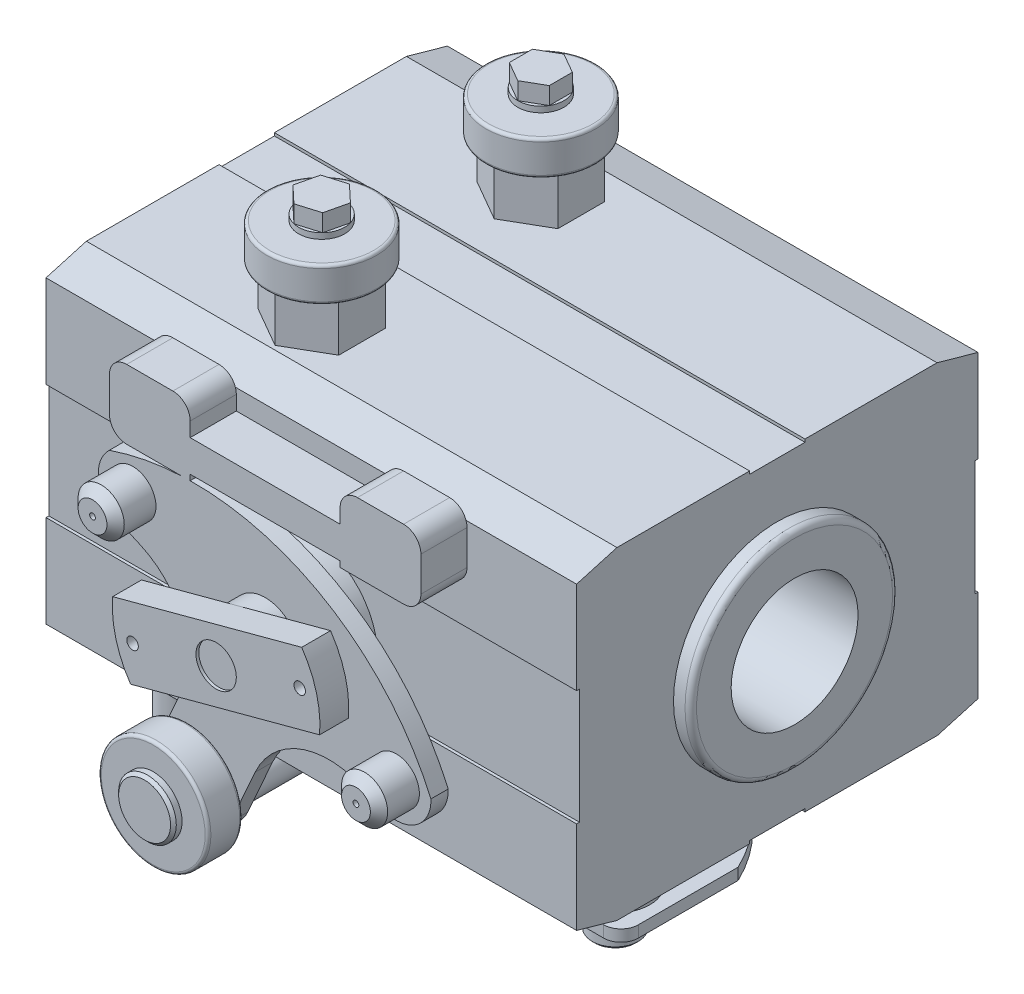
SolidWorks part; units mm, degrees
ref_plane "前视基准面" through (0, 0, 0) normal (0, 0, 1) x (1, 0, 0)
ref_plane "上视基准面" through (0, 0, 0) normal (0, 1, 0) x (1, 0, 0)
ref_plane "右视基准面" through (0, 0, 0) normal (1, 0, 0) x (0, 0, -1)
sketch "草图1" plane through (0, 0, 0) normal (0, 0, 1) x (1, 0, 0)
  line L1 (-73.0162, 7.4225) -> (18.9838, 7.4225)
  line L2 (-73.0162, 7.4225) -> (-73.0162, -48.5775)
  line L3 (-73.0162, -48.5775) -> (18.9838, -48.5775)
  line L4 (18.9838, 7.4225) -> (18.9838, -48.5775)
  dimension "D1" = 56
  dimension "D2" = 92
extrude "拉伸1" add sketch "草图1" along normal blind 69.6
sketch "草图2" plane through (18.9838, 0, 0) normal (1, 0, 0) x (0, 0, -1)
  line L0 (0, -48.5775) -> (0, 7.4225) construction
  line L1 (0, -48.5775) -> (0, -46.5775)
  line L2 (-69.6, 7.4225) -> (0, 7.4225) construction
  line L3 (-69.6, 7.4225) -> (-62.6, 7.4225)
  line L4 (-69.6, -48.5775) -> (-69.6, 7.4225) construction
  line L5 (-69.6, -48.5775) -> (-69.6, -46.5775)
  line L6 (-69.6, -48.5775) -> (0, -48.5775) construction
  line L7 (-69.6, -48.5775) -> (-62.6, -48.5775)
  line L8 (0, 5.4225) -> (-7.1025, 7.4225)
  line L9 (0, -46.5775) -> (-7, -48.5775)
  line L10 (-69.6, 5.4225) -> (-62.6, 7.4225)
  line L11 (-69.6, -46.5775) -> (-62.6, -48.5775)
  line L12 (0, 5.4225) -> (0, 7.4225)
  line L13 (-7.1025, 7.4225) -> (0, 7.4225)
  line L14 (-69.6, 5.4225) -> (-69.6, 7.4225)
  line L15 (-7, -48.5775) -> (0, -48.5775)
  dimension "D1" = 2
  dimension "D2" = 2
  dimension "D3" = 2
  dimension "D4" = 2
  dimension "D5" = 7
  dimension "D6" = 7
  dimension "D7" = 7
extrude "切除-拉伸1" cut sketch "草图2" against normal blind 100
sketch "草图3" plane through (0, -48.5775, 0) normal (0, -1, 0) x (1, 0, 0)
  line L0 (18.9838, 62.6) -> (18.9838, 7) construction
  line L1 (18.9838, 39.6) -> (18.9838, 30)
  line L2 (-73.0162, 62.6) -> (-73.0162, 7) construction
  line L3 (-73.0162, 39.6) -> (-73.0162, 30)
  line L4 (18.9838, 39.6) -> (-73.0162, 39.6)
  line L5 (18.9838, 30) -> (-73.0162, 30)
  line L6 (18.9838, 0) -> (-73.0162, 0) construction
  dimension "D1" = 9.6
  dimension "D2" = 30
extrude "切除-拉伸2" cut sketch "草图3" against normal blind 0.5
sketch "草图4" plane through (0, 7.4225, 0) normal (0, 1, 0) x (-1, 0, 0)
  line L0 (73.0162, 30) -> (-18.9838, 30) construction
  line L1 (73.0162, 30) -> (-18.9838, 30)
  line L2 (-18.9838, 39.6) -> (73.0162, 39.6) construction
  line L3 (-18.9838, 39.6) -> (73.0162, 39.6)
  line L4 (73.0162, 62.6) -> (73.0162, 7.1025) construction
  line L5 (73.0162, 39.6) -> (73.0162, 30)
  line L6 (-18.9838, 62.6) -> (-18.9838, 7.1025) construction
  line L7 (-18.9838, 39.6) -> (-18.9838, 30)
extrude "切除-拉伸3" cut sketch "草图4" against normal blind 0.5
sketch "草图5" plane through (18.9838, 0, 0) normal (1, 0, 0) x (0, 0, -1)
  line L0 (-49.8, 7.4225) -> (-49.8, 2.4225)
  line L1 (-49.8, 2.4225) -> (-19.8, 2.4225)
  line L2 (-19.8, 2.4225) -> (-19.8, 7.4225)
  line L3 (-49.8, -48.5775) -> (-49.8, -43.5775)
  line L4 (-49.8, -43.5775) -> (-19.8, -43.5775)
  line L5 (-19.8, -43.5775) -> (-19.8, -48.5775)
  line L16 (-7.1025, 7.4225) -> (-30, 7.4225)
  line L17 (-30, 7.4225) -> (-30, 6.9225)
  line L18 (-30, 6.9225) -> (-39.6, 6.9225)
  line L19 (-39.6, 6.9225) -> (-39.6, 7.4225)
  line L20 (-39.6, 7.4225) -> (-62.6, 7.4225)
  line L21 (-62.6, 7.4225) -> (-69.6, 5.4225)
  line L22 (-69.6, 5.4225) -> (-69.6, -46.5775)
  line L23 (-69.6, -46.5775) -> (-62.6, -48.5775)
  line L24 (-62.6, -48.5775) -> (-39.6, -48.5775)
  line L25 (-39.6, -48.5775) -> (-39.6, -48.0775)
  line L26 (-39.6, -48.0775) -> (-30, -48.0775)
  line L27 (-30, -48.0775) -> (-30, -48.5775)
  line L28 (-30, -48.5775) -> (-7, -48.5775)
  line L29 (-7, -48.5775) -> (0, -46.5775)
  line L30 (0, -46.5775) -> (0, 5.4225)
  line L31 (0, 5.4225) -> (-7.1025, 7.4225)
  line L32 (-7.1025, 7.4225) -> (-19.8, 7.4225)
  line L36 (-49.8, 7.4225) -> (-62.6, 7.4225)
  line L37 (-62.6, 7.4225) -> (-69.6, 5.4225)
  line L38 (-69.6, 5.4225) -> (-69.6, -46.5775)
  line L39 (-69.6, -46.5775) -> (-62.6, -48.5775)
  line L40 (-62.6, -48.5775) -> (-49.8, -48.5775)
  line L44 (-19.8, -48.5775) -> (-7, -48.5775)
  line L45 (-7, -48.5775) -> (0, -46.5775)
  line L46 (0, -46.5775) -> (0, 5.4225)
  line L47 (0, 5.4225) -> (-7.1025, 7.4225)
  dimension "D2" = 5
  dimension "D3" = 5
  dimension "D4" = 19.8
  dimension "D5" = 30
  dimension "D6" = 30
  dimension "D7" = 19.8
  dimension "D1" = 0
extrude "切除-拉伸4" cut sketch "草图5" against normal blind 3
sketch "草图6" plane through (-73.0162, 0, 0) normal (-1, 0, 0) x (0, 0, 1)
  line L0 (19.8, 2.4225) -> (49.8, 2.4225) construction
  line L1 (19.8, 2.4225) -> (49.8, 2.4225)
  line L2 (49.8, 2.4225) -> (49.8, 7.4225) construction
  line L3 (49.8, 2.4225) -> (49.8, 7.4225)
  line L4 (19.8, 7.4225) -> (19.8, 2.4225) construction
  line L5 (19.8, 7.4225) -> (19.8, 2.4225)
  line L6 (49.8, -43.5775) -> (19.8, -43.5775) construction
  line L7 (49.8, -43.5775) -> (19.8, -43.5775)
  line L8 (49.8, -48.5775) -> (49.8, -43.5775) construction
  line L9 (49.8, -48.5775) -> (49.8, -43.5775)
  line L10 (19.8, -43.5775) -> (19.8, -48.5775) construction
  line L11 (19.8, -43.5775) -> (19.8, -48.5775)
  line L16 (39.6, 6.9225) -> (30, 6.9225)
  line L17 (30, 6.9225) -> (30, 7.4225)
  line L18 (30, 7.4225) -> (7.1025, 7.4225)
  line L19 (7.1025, 7.4225) -> (0, 5.4225)
  line L20 (0, 5.4225) -> (0, -46.5775)
  line L21 (0, -46.5775) -> (7, -48.5775)
  line L22 (7, -48.5775) -> (30, -48.5775)
  line L23 (30, -48.5775) -> (30, -48.0775)
  line L24 (30, -48.0775) -> (39.6, -48.0775)
  line L25 (39.6, -48.0775) -> (39.6, -48.5775)
  line L26 (39.6, -48.5775) -> (62.6, -48.5775)
  line L27 (62.6, -48.5775) -> (69.6, -46.5775)
  line L28 (69.6, -46.5775) -> (69.6, 5.4225)
  line L29 (69.6, 5.4225) -> (62.6, 7.4225)
  line L30 (62.6, 7.4225) -> (39.6, 7.4225)
  line L31 (39.6, 7.4225) -> (39.6, 6.9225)
  line L34 (19.8, 7.4225) -> (7.1025, 7.4225)
  line L35 (7.1025, 7.4225) -> (0, 5.4225)
  line L36 (0, 5.4225) -> (0, -46.5775)
  line L37 (0, -46.5775) -> (7, -48.5775)
  line L38 (7, -48.5775) -> (19.8, -48.5775)
  line L42 (49.8, -48.5775) -> (62.6, -48.5775)
  line L43 (62.6, -48.5775) -> (69.6, -46.5775)
  line L44 (69.6, -46.5775) -> (69.6, 5.4225)
  line L45 (69.6, 5.4225) -> (62.6, 7.4225)
  line L46 (62.6, 7.4225) -> (49.8, 7.4225)
  dimension "D1" = 0
extrude "切除-拉伸5" cut sketch "草图6" against normal blind 3
sketch "草图7" plane through (-70.0162, 0, 0) normal (-1, 0, 0) x (0, 0, 1)
  line L1 (69.6, -46.5775) -> (69.6, 5.4225) construction
  line L3 (62.6, 7.4225) -> (49.8, 7.4225) construction
  circle A0 centre (34.8, -20.5775) radius 11
  dimension "D1" = 22
  dimension "D3" = 28
  dimension "D2" = 34.8
extrude "切除-拉伸6" cut sketch "草图7" against normal blind 100
sketch "草图10" plane through (0, 0, 0) normal (0, 0, -1) x (-1, 0, 0)
  line L3 (70.0162, -48.5775) -> (-15.9838, -48.5775) construction
  line L4 (52.0162, -38.5775) -> (2.0162, -38.5775) construction
  line L5 (52.0162, -38.5775) -> (52.0162, -2.5775) construction
  line L6 (70.0162, 5.4225) -> (70.0162, -46.5775) construction
  circle A0 centre (52.0162, -38.5775) radius 3
  circle A1 centre (2.0162, -38.5775) radius 3
  circle A2 centre (52.0162, -2.5775) radius 3
  circle A3 centre (2.0162, -2.5775) radius 3
  dimension "D1" = 18
  dimension "D2" = 10
  dimension "D3" = 90
  dimension "D4" = 50
extrude "切除-拉伸8" cut sketch "草图10" against normal blind 15
sketch "草图11" plane through (0, 0, 0) normal (0, 0, -1) x (-1, 0, 0)
  line L0 (70.0162, 5.4225) -> (70.0162, -46.5775) construction
  line L1 (70.0162, -10.5775) -> (70.0162, -30.5775)
  line L2 (-15.9838, -46.5775) -> (-15.9838, 5.4225) construction
  line L3 (-15.9838, -30.5775) -> (-15.9838, -10.5775)
  line L4 (-15.9838, -10.5775) -> (70.0162, -10.5775)
  line L5 (-15.9838, -30.5775) -> (70.0162, -30.5775)
  line L6 (70.0162, 7.4225) -> (-15.9838, 7.4225) construction
  dimension "D1" = 18
  dimension "D2" = 20
extrude "切除-拉伸9" cut sketch "草图11" against normal blind 0.5
sketch "草图12" plane through (0, 0, 69.6) normal (0, 0, 1) x (1, 0, 0)
  line L0 (-70.0162, -10.5775) -> (15.9838, -10.5775) construction
  line L1 (-70.0162, -10.5775) -> (15.9838, -10.5775)
  line L2 (15.9838, -30.5775) -> (-70.0162, -30.5775) construction
  line L3 (15.9838, -30.5775) -> (-70.0162, -30.5775)
  line L4 (15.9838, 5.4225) -> (15.9838, -46.5775) construction
  line L5 (15.9838, -10.5775) -> (15.9838, -30.5775)
  line L6 (-70.0162, -46.5775) -> (-70.0162, 5.4225) construction
  line L7 (-70.0162, -30.5775) -> (-70.0162, -10.5775)
extrude "切除-拉伸10" cut sketch "草图12" against normal blind 0.5
sketch "草图14" plane through (0, -48.5775, 0) normal (0, -1, 0) x (1, 0, 0)
  line L1 (18.9838, 49.8) -> (18.9838, 39.6) construction
  line L2 (15.9838, 69.6) -> (-70.0162, 69.6) construction
  circle A0 centre (-15.5162, 48.4) radius 8
  dimension "D1" = 34.5
  dimension "D2" = 21.2
extrude "切除-拉伸11" cut sketch "草图14" against normal blind 20
sketch "草图15" plane through (0, -48.5775, 0) normal (0, -1, 0) x (1, 0, 0)
  line L0 (15.9838, 69.6) -> (-70.0162, 69.6) construction
  line L1 (-70.0162, 49.8) -> (-70.0162, 62.6) construction
  circle A0 centre (-54.8162, 65.1) radius 3
  dimension "D1" = 4.5
  dimension "D2" = 15.2
extrude "切除-拉伸12" cut sketch "草图15" against normal blind 100
sketch "草图17" plane through (0, -48.5775, 0) normal (0, -1, 0) x (1, 0, 0)
  circle A0 centre (-35.5162, 48.4) radius 2
  circle A1 centre (4.4838, 48.4) radius 2
  circle A2 centre (-15.5162, 48.4) radius 8 construction
  dimension "D1" = 20
  dimension "D2" = 20
extrude "切除-拉伸14" cut sketch "草图17" against normal blind 10
sketch "草图18" plane through (0, -48.5775, 0) normal (0, -1, 0) x (1, 0, 0)
  circle A0 centre (-15.5162, 48.4) radius 9
extrude "拉伸2" add sketch "草图18" along normal blind 5
sketch "草图19" plane through (0, -53.5775, 0) normal (0, -1, 0) x (1, 0, 0)
  circle A0 centre (-15.5162, 48.4) radius 1.5
extrude "切除-拉伸15" cut sketch "草图19" against normal blind 10
sketch "草图20" plane through (0, -53.5775, 0) normal (0, -1, 0) x (1, 0, 0)
  circle A1 centre (-15.5162, 48.4) radius 9
  circle A2 centre (-15.5162, 48.4) radius 9
  dimension "D1" = 0
extrude "切除-拉伸16" cut sketch "草图20" against normal blind 2
sketch "草图21" plane through (0, 7.4225, 0) normal (0, 1, 0) x (-1, 0, 0)
  line L0 (70.0162, 19.8) -> (70.0162, 7.1025) construction
  line L1 (70.0162, 0) -> (-15.9838, 0) construction
  line L4 (70.0162, 69.6) -> (-15.9838, 69.6) construction
  line L5 (70.0162, 62.6) -> (70.0162, 49.8) construction
  circle A0 centre (41.0162, 15.8) radius 4
  circle A1 centre (41.0162, 53.8) radius 4
  dimension "D1" = 29
  dimension "D3" = 15.8
  dimension "D2" = 15.8
  dimension "D4" = 29
extrude "切除-拉伸17" cut sketch "草图21" against normal blind 10
sketch "草图23" plane through (0, 0, 69.6) normal (0, 0, 1) x (1, 0, 0)
  line L6 (-53.1579, 7.4225) -> (15.9838, 7.4225) construction
  line L11 (18.9838, 2.4225) -> (18.9838, 7.4225) construction
  line L12 (-73.0162, 7.4225) -> (-73.0162, 2.4225) construction
  circle A0 centre (-8.0162, 1.4225) radius 2.5
  circle A1 centre (-46.0162, 1.4225) radius 2.5
  dimension "D1" = 6
  dimension "D2" = 6
  dimension "D3" = 27
  dimension "D4" = 27
extrude "切除-拉伸19" cut sketch "草图23" against normal blind 6
sketch "草图24" plane through (15.9838, 0, 0) normal (1, 0, 0) x (0, 0, -1)
  line L24 (-69.6, 5.4225) -> (-69.6, -10.5775)
  line L25 (-69.6, -10.5775) -> (-69.1, -10.5775)
  line L26 (-69.1, -10.5775) -> (-69.1, -30.5775)
  line L27 (-69.1, -30.5775) -> (-69.6, -30.5775)
  line L28 (-69.6, -30.5775) -> (-69.6, -46.5775)
  line L29 (-69.6, -46.5775) -> (-62.6, -48.5775)
  line L30 (-62.6, -48.5775) -> (-49.8, -48.5775)
  line L31 (-49.8, -48.5775) -> (-49.8, -43.5775)
  line L32 (-49.8, -43.5775) -> (-19.8, -43.5775)
  line L33 (-19.8, -43.5775) -> (-19.8, -48.5775)
  line L34 (-19.8, -48.5775) -> (-7, -48.5775)
  line L35 (-7, -48.5775) -> (0, -46.5775)
  line L36 (0, -46.5775) -> (0, -30.5775)
  line L37 (0, -30.5775) -> (-0.5, -30.5775)
  line L38 (-0.5, -30.5775) -> (-0.5, -10.5775)
  line L39 (-0.5, -10.5775) -> (0, -10.5775)
  line L40 (0, -10.5775) -> (0, 5.4225)
  line L41 (0, 5.4225) -> (-7.1025, 7.4225)
  line L42 (-7.1025, 7.4225) -> (-19.8, 7.4225)
  line L43 (-19.8, 7.4225) -> (-19.8, 2.4225)
  line L44 (-19.8, 2.4225) -> (-49.8, 2.4225)
  line L45 (-49.8, 2.4225) -> (-49.8, 7.4225)
  line L46 (-49.8, 7.4225) -> (-62.6, 7.4225)
  line L47 (-62.6, 7.4225) -> (-69.6, 5.4225)
  line L48 (-69.6, 5.4225) -> (-69.6, -10.5775)
  line L49 (-69.6, -10.5775) -> (-69.1, -10.5775)
  line L50 (-69.1, -10.5775) -> (-69.1, -30.5775)
  line L51 (-69.1, -30.5775) -> (-69.6, -30.5775)
  line L52 (-69.6, -30.5775) -> (-69.6, -46.5775)
  line L53 (-69.6, -46.5775) -> (-62.6, -48.5775)
  line L54 (-62.6, -48.5775) -> (-49.8, -48.5775)
  line L55 (-49.8, -48.5775) -> (-49.8, -43.5775)
  line L56 (-49.8, -43.5775) -> (-19.8, -43.5775)
  line L57 (-19.8, -43.5775) -> (-19.8, -48.5775)
  line L58 (-19.8, -48.5775) -> (-7, -48.5775)
  line L59 (-7, -48.5775) -> (0, -46.5775)
  line L60 (0, -46.5775) -> (0, -30.5775)
  line L61 (0, -30.5775) -> (-0.5, -30.5775)
  line L62 (-0.5, -30.5775) -> (-0.5, -10.5775)
  line L63 (-0.5, -10.5775) -> (0, -10.5775)
  line L64 (0, -10.5775) -> (0, 5.4225)
  line L65 (0, 5.4225) -> (-7.1025, 7.4225)
  line L66 (-7.1025, 7.4225) -> (-19.8, 7.4225)
  line L67 (-19.8, 7.4225) -> (-19.8, 2.4225)
  line L68 (-19.8, 2.4225) -> (-49.8, 2.4225)
  line L69 (-49.8, 2.4225) -> (-49.8, 7.4225)
  line L70 (-49.8, 7.4225) -> (-62.6, 7.4225)
  line L71 (-62.6, 7.4225) -> (-69.6, 5.4225)
  circle A0 centre (-34.8, -20.5775) radius 11 construction
  circle A1 centre (-34.8, -20.5775) radius 11
  dimension "D1" = 0
extrude "拉伸3" add sketch "草图24" along normal blind 3
sketch "草图25" plane through (-70.0162, 0, 0) normal (-1, 0, 0) x (0, 0, 1)
  line L24 (69.1, -10.5775) -> (69.6, -10.5775)
  line L25 (69.6, -10.5775) -> (69.6, 5.4225)
  line L26 (69.6, 5.4225) -> (62.6, 7.4225)
  line L27 (62.6, 7.4225) -> (49.8, 7.4225)
  line L28 (49.8, 7.4225) -> (49.8, 2.4225)
  line L29 (49.8, 2.4225) -> (19.8, 2.4225)
  line L30 (19.8, 2.4225) -> (19.8, 7.4225)
  line L31 (19.8, 7.4225) -> (7.1025, 7.4225)
  line L32 (7.1025, 7.4225) -> (0, 5.4225)
  line L33 (0, 5.4225) -> (0, -10.5775)
  line L34 (0, -10.5775) -> (0.5, -10.5775)
  line L35 (0.5, -10.5775) -> (0.5, -30.5775)
  line L36 (0.5, -30.5775) -> (0, -30.5775)
  line L37 (0, -30.5775) -> (0, -46.5775)
  line L38 (0, -46.5775) -> (7, -48.5775)
  line L39 (7, -48.5775) -> (19.8, -48.5775)
  line L40 (19.8, -48.5775) -> (19.8, -43.5775)
  line L41 (19.8, -43.5775) -> (49.8, -43.5775)
  line L42 (49.8, -43.5775) -> (49.8, -48.5775)
  line L43 (49.8, -48.5775) -> (62.6, -48.5775)
  line L44 (62.6, -48.5775) -> (69.6, -46.5775)
  line L45 (69.6, -46.5775) -> (69.6, -30.5775)
  line L46 (69.6, -30.5775) -> (69.1, -30.5775)
  line L47 (69.1, -30.5775) -> (69.1, -10.5775)
  line L48 (69.1, -10.5775) -> (69.6, -10.5775)
  line L49 (69.6, -10.5775) -> (69.6, 5.4225)
  line L50 (69.6, 5.4225) -> (62.6, 7.4225)
  line L51 (62.6, 7.4225) -> (49.8, 7.4225)
  line L52 (49.8, 7.4225) -> (49.8, 2.4225)
  line L53 (49.8, 2.4225) -> (19.8, 2.4225)
  line L54 (19.8, 2.4225) -> (19.8, 7.4225)
  line L55 (19.8, 7.4225) -> (7.1025, 7.4225)
  line L56 (7.1025, 7.4225) -> (0, 5.4225)
  line L57 (0, 5.4225) -> (0, -10.5775)
  line L58 (0, -10.5775) -> (0.5, -10.5775)
  line L59 (0.5, -10.5775) -> (0.5, -30.5775)
  line L60 (0.5, -30.5775) -> (0, -30.5775)
  line L61 (0, -30.5775) -> (0, -46.5775)
  line L62 (0, -46.5775) -> (7, -48.5775)
  line L63 (7, -48.5775) -> (19.8, -48.5775)
  line L64 (19.8, -48.5775) -> (19.8, -43.5775)
  line L65 (19.8, -43.5775) -> (49.8, -43.5775)
  line L66 (49.8, -43.5775) -> (49.8, -48.5775)
  line L67 (49.8, -48.5775) -> (62.6, -48.5775)
  line L68 (62.6, -48.5775) -> (69.6, -46.5775)
  line L69 (69.6, -46.5775) -> (69.6, -30.5775)
  line L70 (69.6, -30.5775) -> (69.1, -30.5775)
  line L71 (69.1, -30.5775) -> (69.1, -10.5775)
  circle A0 centre (34.8, -20.5775) radius 11 construction
  circle A1 centre (34.8, -20.5775) radius 11
  dimension "D1" = 0
extrude "拉伸4" add sketch "草图25" along normal blind 3
sketch "草图26" plane through (-73.0162, 0, 0) normal (-1, 0, 0) x (0, 0, 1)
  circle A0 centre (34.8, -20.5775) radius 18
  circle A1 centre (34.8, -20.5775) radius 11 construction
  circle A2 centre (34.8, -20.5775) radius 11
extrude "拉伸5" add sketch "草图26" along normal blind 3
sketch "草图27" plane through (18.9838, 0, 0) normal (1, 0, 0) x (0, 0, -1)
  circle A0 centre (-34.8, -20.5775) radius 18
  circle A1 centre (-34.8, -20.5775) radius 11 construction
  circle A2 centre (-34.8, -20.5775) radius 11
extrude "拉伸6" add sketch "草图27" along normal blind 3
fillet "圆角1" radius 1 2 edges at (-76.0162, -20.5775, 52.8) (21.9838, -20.5775, 16.8)
sketch "草图28" plane through (0, -48.5775, 0) normal (0, -1, 0) x (1, 0, 0)
  circle A0 centre (4.4838, 48.4) radius 6
  circle A1 centre (-35.5162, 48.4) radius 6
extrude "拉伸7" add sketch "草图28" along normal blind 9
sketch "草图29" plane through (0, -51.5775, 0) normal (0, -1, 0) x (1, 0, 0)
  circle A1 centre (-15.5162, 48.4) radius 9
  circle A2 centre (-15.5162, 48.4) radius 9
  dimension "D1" = 0
extrude "拉伸8" add sketch "草图29" along normal blind 5
sketch "草图30" plane through (0, -56.5775, 0) normal (0, -1, 0) x (1, 0, 0)
  line L0 (-15.9113, 56.7698) -> (-11.4651, 55.7348)
  line L1 (-17.6313, 56.9563) -> (-29.3268, 6.7164)
  line L2 (-9.8396, 55.1425) -> (-21.5352, 4.9025)
  line L3 (-27.7013, 6.124) -> (-23.2552, 5.089)
  arc A1 (-29.3268, 6.7164) -> (-27.7013, 6.124) centre (-19.5832, 30.9294) ccw
  arc A2 (-9.8396, 55.1425) -> (-11.4651, 55.7348) centre (-19.5832, 30.9294) ccw
  arc A3 (-23.2552, 5.089) -> (-21.5352, 4.9025) centre (-19.5832, 30.9294) ccw
  arc A4 (-15.9113, 56.7698) -> (-17.6313, 56.9563) centre (-19.5832, 30.9294) ccw
  dimension "D1" = 8
  dimension "D2" = 52
extrude "拉伸9" add sketch "草图30" along normal blind 1
sketch "草图31" plane through (0, -57.5775, 0) normal (0, -1, 0) x (1, 0, 0)
  line L0 (-3.5162, 48.4) -> (-3.5162, 50.4)
  line L1 (9.4838, 55.4) -> (1.4838, 55.4)
  line L2 (12.4838, 52.4) -> (12.4838, 35.0959)
  line L3 (-27.5162, 48.4) -> (-27.5162, 50.4)
  line L4 (-43.5162, 52.4) -> (-43.5162, 35.0959)
  line L5 (-32.5162, 55.4) -> (-40.5162, 55.4)
  arc A0 (-32.5162, 55.4) -> (-27.5162, 50.4) centre (-32.5162, 50.4) cw
  arc A1 (-13.4483, 39.6408) -> (-21.24, 41.4546) centre (-15.5162, 48.4) ccw construction
  circle A2 centre (-15.5162, 48.4) radius 8 construction
  arc A3 (-43.5162, 35.0959) -> (12.4838, 35.0959) centre (-15.5162, 48.4) ccw
  arc A4 (-27.5162, 48.4) -> (-3.5162, 48.4) centre (-15.5162, 48.4) ccw
  arc A5 (1.4838, 55.4) -> (-3.5162, 50.4) centre (1.4838, 50.4) ccw
  arc A6 (-40.5162, 55.4) -> (-43.5162, 52.4) centre (-40.5162, 52.4) ccw
  arc A7 (9.4838, 55.4) -> (12.4838, 52.4) centre (9.4838, 52.4) cw
  point P16 (-27.5162, 55.4)
  dimension "D1" = 28
  dimension "D2" = 28
  dimension "D4" = 5
  dimension "D5" = 3
  dimension "D3" = 7
extrude "拉伸10" add sketch "草图31" along normal blind 2
sketch "草图32" plane through (0, -59.5775, 0) normal (0, -1, 0) x (1, 0, 0)
  circle A0 centre (4.4838, 48.4) radius 4
  circle A1 centre (-35.5162, 48.4) radius 4
extrude "拉伸11" add sketch "草图32" along normal blind 5
sketch "草图33" plane through (0, -64.5775, 0) normal (0, -1, 0) x (1, 0, 0)
  line L1 (-33.7841, 48.4) -> (-34.6502, 49.9)
  line L2 (-34.6502, 49.9) -> (-36.3822, 49.9)
  line L3 (-36.3822, 49.9) -> (-37.2482, 48.4)
  line L4 (-37.2482, 48.4) -> (-36.3822, 46.9)
  line L5 (-36.3822, 46.9) -> (-34.6502, 46.9)
  line L6 (-34.6502, 46.9) -> (-33.7841, 48.4)
  line L7 (5.0589, 46.7662) -> (6.1863, 48.0811)
  line L8 (6.1863, 48.0811) -> (5.6112, 49.7149)
  line L9 (5.6112, 49.7149) -> (3.9087, 50.0338)
  line L10 (3.9087, 50.0338) -> (2.7814, 48.7189)
  line L11 (2.7814, 48.7189) -> (3.3564, 47.0851)
  line L12 (3.3564, 47.0851) -> (5.0589, 46.7662)
  circle A0 centre (-35.5162, 48.4) radius 1.5 construction
  circle A1 centre (4.4838, 48.4) radius 1.5 construction
  dimension "D1" = 3
  dimension "D2" = 3
extrude "切除-拉伸20" cut sketch "草图33" against normal blind 3
chamfer "倒角1" distance 0.5 angle 45 2 edges at (4.4838, -64.5775, 44.4) (-35.5162, -64.5775, 44.4)
sketch "草图34" plane through (0, -57.5775, 0) normal (0, -1, 0) x (1, 0, 0)
  line L3 (-26.3819, 19.3666) -> (-29.3268, 6.7164)
  line L4 (-27.7013, 6.124) -> (-23.2552, 5.089)
  line L5 (-21.5352, 4.9025) -> (-18.5903, 17.5528)
  line L6 (-26.3819, 19.3666) -> (-29.3268, 6.7164)
  line L7 (-27.7013, 6.124) -> (-23.2552, 5.089)
  line L8 (-21.5352, 4.9025) -> (-18.5903, 17.5528)
  arc A3 (-26.3819, 19.3666) -> (-18.5903, 17.5528) centre (-15.5162, 48.4) ccw
  arc A4 (-29.3268, 6.7164) -> (-27.7013, 6.124) centre (-19.5832, 30.9294) ccw
  arc A5 (-23.2552, 5.089) -> (-21.5352, 4.9025) centre (-19.5832, 30.9294) ccw
  arc A6 (-26.3819, 19.3666) -> (-18.5903, 17.5528) centre (-15.5162, 48.4) ccw
  arc A7 (-29.3268, 6.7164) -> (-27.7013, 6.124) centre (-19.5832, 30.9294) ccw
  arc A8 (-23.2552, 5.089) -> (-21.5352, 4.9025) centre (-19.5832, 30.9294) ccw
  dimension "D1" = 0
extrude "拉伸12" add sketch "草图34" along normal blind 2
sketch "草图35" plane through (0, -59.5775, 0) normal (0, -1, 0) x (1, 0, 0)
  line L0 (-27.7013, 6.124) -> (-23.2552, 5.089) construction
  line L1 (-27.7013, 6.124) -> (-23.2552, 5.089)
  line L2 (-21.5352, 4.9025) -> (-18.5903, 17.5528) construction
  line L3 (-21.5352, 4.9025) -> (-18.5903, 17.5528)
  line L4 (-26.3819, 19.3666) -> (-29.3268, 6.7164) construction
  line L5 (-26.3819, 19.3666) -> (-29.3268, 6.7164)
  line L6 (-21.5352, 20.4951) -> (-21.0831, 17.9039)
  line L7 (-21.5352, 20.4951) -> (-23.0563, 18.331)
  arc A0 (-29.3268, 6.7164) -> (-27.7013, 6.124) centre (-19.5832, 30.9294) ccw construction
  arc A1 (-29.3268, 6.7164) -> (-27.7013, 6.124) centre (-19.5832, 30.9294) ccw
  arc A2 (-23.2552, 5.089) -> (-21.5352, 4.9025) centre (-19.5832, 30.9294) ccw construction
  arc A3 (-23.2552, 5.089) -> (-21.5352, 4.9025) centre (-19.5832, 30.9294) ccw
  arc A4 (-18.5903, 17.5528) -> (12.4838, 35.0959) centre (-15.5162, 48.4) ccw construction
  arc A5 (-26.3819, 19.3666) -> (-23.0563, 18.331) centre (-15.5162, 48.4) ccw
  arc A6 (-21.0831, 17.9039) -> (-18.5903, 17.5528) centre (-15.5162, 48.4) ccw
extrude "拉伸13" add sketch "草图35" along normal blind 0.5
sketch "草图36" plane through (0, -48.5775, 0) normal (0, -1, 0) x (1, 0, 0)
  arc A0 (-53.1579, 62.6) -> (-56.4745, 62.6) centre (-54.8162, 65.1) ccw construction
  arc A1 (-53.1579, 62.6) -> (-56.4745, 62.6) centre (-54.8162, 65.1) ccw
  arc A2 (-56.4745, 62.6) -> (-53.1579, 62.6) centre (-54.8162, 65.1) ccw construction
  arc A3 (-56.4745, 62.6) -> (-53.1579, 62.6) centre (-54.8162, 65.1) ccw
ref_plane "基准面1" through (-54.82, 0, 0) normal (1, 0, 0) x (0, 0, -1)
sketch "草图37" plane through (-54.82, 0, 0) normal (1, 0, 0) x (0, 0, -1)
  line L0 (-65.0156, -34.5775) -> (-65.0156, -59.5775)
  line L1 (-56.0156, -68.5775) -> (-40.0156, -68.5775)
  line L2 (-62.6, -48.5775) -> (-39.6, -48.5775) construction
  arc A0 (-56.0156, -68.5775) -> (-65.0156, -59.5775) centre (-56.0156, -59.5775) cw
  point P5 (-65.0156, -68.5775)
  dimension "D3" = 9
  dimension "D1" = 25
  dimension "D2" = 25
  dimension "D4" = 20
sweep "扫描3" add profiles "草图36" path "草图37"
sketch "草图38" plane through (0, 7.4225, 0) normal (0, 1, 0) x (-1, 0, 0)
  arc A0 (56.4745, 62.6) -> (53.1579, 62.6) centre (54.8162, 65.1) ccw construction
  arc A1 (56.4745, 62.6) -> (53.1579, 62.6) centre (54.8162, 65.1) ccw
  arc A2 (53.1579, 62.6) -> (56.4745, 62.6) centre (54.8162, 65.1) ccw construction
  arc A3 (53.1579, 62.6) -> (56.4745, 62.6) centre (54.8162, 65.1) ccw
extrude "拉伸14" add sketch "草图38" against normal blind 56
sketch "草图39" plane through (-73.0162, 0, 0) normal (-1, 0, 0) x (0, 0, 1)
  line L0 (69.6, 5.4225) -> (62.6, 7.4225) construction
  line L1 (69.6, 5.4225) -> (62.6, 7.4225)
  line L2 (68.1, 7.4225) -> (62.6, 7.4225) construction
  line L3 (69.6, 7.4225) -> (62.6, 7.4225)
  line L4 (69.6, -10.5775) -> (69.6, 5.4225) construction
  line L5 (69.6, 5.4225) -> (69.6, 7.4225)
extrude "切除-拉伸21" cut sketch "草图39" against normal blind 100
chamfer "倒角2" distance 0.5 angle 45 1 edges at (-54.8162, -65.6619, 40.0156)
sketch "草图40" plane through (0, 0, 69.6) normal (0, 0, 1) x (1, 0, 0)
  line L0 (-40.0162, -3.5775) -> (-14.0162, -3.5775)
  line L1 (-51.0162, 7.4225) -> (-43.0162, 7.4225)
  line L2 (-54.0162, 4.4225) -> (-54.0162, -1.5775)
  line L3 (-14.0162, -4.5775) -> (-3.0162, -4.5775)
  line L4 (-0.0162, 4.4225) -> (-0.0162, -1.5775)
  line L6 (-14.0162, 1.9225) -> (-14.0162, 4.4225)
  line L7 (-40.0162, -3.5775) -> (-40.0162, -4.5775)
  line L8 (-40.0162, 4.4225) -> (-40.0162, 1.9225)
  line L9 (-40.0162, 1.9225) -> (-14.0162, 1.9225)
  line L10 (-14.0162, -4.5775) -> (-14.0162, -3.5775)
  line L12 (-11.0162, 7.4225) -> (-3.0162, 7.4225)
  line L14 (-51.0162, -4.5775) -> (-40.0162, -4.5775)
  circle A1 centre (-46.0162, 1.4225) radius 2.5 construction
  circle A4 centre (-8.0162, 1.4225) radius 2.5 construction
  arc A6 (-51.0162, 7.4225) -> (-54.0162, 4.4225) centre (-51.0162, 4.4225) ccw
  arc A7 (-40.0162, 4.4225) -> (-43.0162, 7.4225) centre (-43.0162, 4.4225) ccw
  arc A10 (-3.0162, 7.4225) -> (-0.0162, 4.4225) centre (-3.0162, 4.4225) cw
  arc A11 (-14.0162, 4.4225) -> (-11.0162, 7.4225) centre (-11.0162, 4.4225) cw
  arc A12 (-3.0162, -4.5775) -> (-0.0162, -1.5775) centre (-3.0162, -1.5775) ccw
  arc A13 (-51.0162, -4.5775) -> (-54.0162, -1.5775) centre (-51.0162, -1.5775) cw
  point P30 (-14.0162, 7.4225)
  dimension "D1" = 6
  dimension "D6" = 6
  dimension "D8" = 1
  dimension "D9" = 3
  dimension "D10" = 3
  dimension "D2" = 8
  dimension "D3" = 6
  dimension "D4" = 5.5
  dimension "D5" = 8
  dimension "D7" = 6
extrude "拉伸15" add sketch "草图40" along normal blind 8
sketch "草图42" plane through (0, 0, 69.1) normal (0, 0, 1) x (1, 0, 0)
  line L1 (18.9838, -10.5775) -> (18.9838, -30.5775) construction
  line L7 (-53.1579, -48.5775) -> (18.9838, -48.5775) construction
  circle A0 centre (-27.0162, -21.5775) radius 3.5
  dimension "D1" = 46
  dimension "D2" = 27
extrude "拉伸17" add sketch "草图42" along normal blind 1.5
sketch "草图43" plane through (0, 0, 70.6) normal (0, 0, 1) x (1, 0, 0)
  circle A0 centre (-27.0162, -21.5775) radius 12.5
extrude "拉伸18" add sketch "草图43" along normal blind 4
sketch "草图44" plane through (0, 0, 74.6) normal (0, 0, 1) x (1, 0, 0)
  line L1 (-48.6456, -18.5175) -> (-52.295, -16.894)
  line L5 (-6.8066, -37.1309) -> (-10.2717, -35.5893)
  line L10 (-28.752, -42.6863) -> (-33.0268, -52.2878)
  line L12 (-41.5466, -37.0032) -> (-45.8165, -46.5935)
  arc A0 (1.7221, -31.4629) -> (-54.0425, -6.9878) centre (-39.4216, -49.4406) ccw
  arc A1 (-6.8066, -37.1309) -> (1.7221, -31.4629) centre (-4.2735, -31.6918) ccw
  circle A2 centre (-27.0162, -21.5775) radius 12.5 construction
  arc A3 (-45.8165, -46.5935) -> (-33.0268, -52.2878) centre (-39.4216, -49.4406) ccw
  arc A4 (-54.0425, -6.9878) -> (-52.295, -16.894) centre (-49.9469, -11.3726) ccw
  arc A5 (-10.2717, -35.5893) -> (-28.752, -42.6863) centre (-15.9623, -48.3806) ccw
  arc A6 (-48.6456, -18.5175) -> (-41.5466, -37.0032) centre (-54.3362, -31.3088) cw
  point P23 (-35.8506, -24.2098)
  point P34 (-35.8585, -24.2276)
  dimension "D2" = 30.5
  dimension "D3" = 14
  dimension "D7" = 89.8
extrude "拉伸19" add sketch "草图44" along normal blind 3
sketch "草图45" plane through (0, 0, 77.6) normal (0, 0, 1) x (1, 0, 0)
  circle A0 centre (-39.4216, -49.4406) radius 3.5
extrude "拉伸20" add sketch "草图45" along normal blind 1
sketch "草图46" plane through (0, 0, 78.6) normal (0, 0, 1) x (1, 0, 0)
  circle A0 centre (-39.4216, -49.4406) radius 9.5
extrude "拉伸21" add sketch "草图46" along normal blind 6
fillet "圆角3" radius 0.5 2 edges at (-29.9216, -49.4406, 84.6) (-29.9216, -49.4406, 78.6)
sketch "草图48" plane through (0, 0, 84.6) normal (0, 0, 1) x (1, 0, 0)
  circle A0 centre (-39.4216, -49.4406) radius 5
extrude "拉伸22" add sketch "草图48" along normal blind 1.5
chamfer "倒角3" distance 0.5 angle 45 1 edges at (-34.4216, -49.4406, 86.1)
sketch "草图49" plane through (0, 0, 77.6) normal (0, 0, 1) x (1, 0, 0)
  circle A0 centre (-4.2735, -31.6918) radius 4
  circle A1 centre (-49.9469, -11.3726) radius 4
extrude "拉伸23" add sketch "草图49" along normal blind 7
chamfer "倒角4" distance 1.5 angle 45 2 edges at (-45.9469, -11.3726, 84.6) (-0.2735, -31.6918, 84.6)
sketch "草图50" plane through (0, 0, 84.6) normal (0, 0, 1) x (1, 0, 0)
  circle A0 centre (-4.2735, -31.6918) radius 0.5
  circle A1 centre (-49.9469, -11.3726) radius 0.5
extrude "切除-拉伸22" cut sketch "草图50" against normal blind 3
sketch "草图51" plane through (0, 0, 77.6) normal (0, 0, 1) x (1, 0, 0)
  circle A0 centre (-27.0162, -21.5775) radius 6
extrude "拉伸24" add sketch "草图51" along normal blind 3.5
sketch "草图53" plane through (0, 0, 81.1) normal (0, 0, 1) x (1, 0, 0)
  line L1 (-41.8556, -31.7654) -> (-9.071, -22.9808)
  line L2 (-44.9614, -20.1742) -> (-12.1768, -11.3896)
  arc A0 (-9.071, -22.9808) -> (-12.1768, -11.3896) centre (-27.0162, -21.5775) ccw
  arc A3 (-44.9614, -20.1742) -> (-41.8556, -31.7654) centre (-27.0162, -21.5775) ccw
  dimension "D1" = 12
extrude "拉伸27" add sketch "草图53" along normal blind 5
sketch "草图55" plane through (0, 0, 86.1) normal (0, 0, 1) x (1, 0, 0)
  circle A0 centre (-27.0162, -21.5775) radius 3.5
extrude "切除-拉伸23" cut sketch "草图55" against normal blind 0.5
sketch "草图56" plane through (0, 0, 86.1) normal (0, 0, 1) x (1, 0, 0)
  line L0 (-41.8556, -31.7654) -> (-9.071, -22.9808) construction
  circle A0 centre (-12.5273, -17.6952) radius 1
  circle A1 centre (-41.5051, -25.4598) radius 1
  circle A4 centre (-27.0162, -21.5775) radius 3.5 construction
  dimension "D1" = 6
  dimension "D3" = 15
  dimension "D4" = 15
  dimension "D2" = 6
extrude "切除-拉伸24" cut sketch "草图56" against normal blind 5
sketch "草图57" plane through (0, 7.4225, 0) normal (0, 1, 0) x (-1, 0, 0)
  line L0 (73.0162, 39.6) -> (-18.9838, 39.6) construction
  line L1 (48.0162, 57.8415) -> (41.0162, 61.8829)
  line L2 (41.0162, 61.8829) -> (34.0162, 57.8415)
  line L3 (34.0162, 57.8415) -> (34.0162, 49.7585)
  line L4 (34.0162, 49.7585) -> (41.0162, 45.7171)
  line L5 (41.0162, 45.7171) -> (48.0162, 49.7585)
  line L6 (48.0162, 49.7585) -> (48.0162, 57.8415)
  line L7 (48.0162, 19.8415) -> (41.0162, 23.8829)
  line L8 (41.0162, 23.8829) -> (34.0162, 19.8415)
  line L9 (34.0162, 19.8415) -> (34.0162, 11.7585)
  line L10 (34.0162, 11.7585) -> (41.0162, 7.7171)
  line L11 (41.0162, 7.7171) -> (48.0162, 11.7585)
  line L12 (48.0162, 11.7585) -> (48.0162, 19.8415)
  line L13 (-18.9838, 30) -> (73.0162, 30) construction
  circle A0 centre (41.0162, 53.8) radius 7 construction
  circle A1 centre (41.0162, 15.8) radius 7 construction
  dimension "D1" = 90
  dimension "D2" = 90
  dimension "D3" = 14
  dimension "D4" = 14
extrude "拉伸29" add sketch "草图57" along normal blind 8
sketch "草图60" plane through (0, 15.4225, 0) normal (0, 1, 0) x (-1, 0, 0)
  circle A0 centre (41.0162, 53.8) radius 3.5
  circle A1 centre (41.0162, 15.8) radius 3.5
extrude "拉伸31" add sketch "草图60" along normal blind 0.7
sketch "草图61" plane through (0, 16.1225, 0) normal (0, 1, 0) x (-1, 0, 0)
  circle A0 centre (41.0162, 53.8) radius 9.5
  circle A1 centre (41.0162, 15.8) radius 9.5
extrude "拉伸32" add sketch "草图61" along normal blind 6
fillet "圆角4" radius 0.5 4 edges at (-41.0162, 16.1225, 63.3) (-41.0162, 22.1225, 63.3) (-41.0162, 16.1225, 25.3) (-41.0162, 22.1225, 25.3)
sketch "草图62" plane through (0, 22.1225, 0) normal (0, 1, 0) x (-1, 0, 0)
  circle A0 centre (41.0162, 53.8) radius 4
  circle A1 centre (41.0162, 15.8) radius 4
extrude "拉伸33" add sketch "草图62" along normal blind 1
sketch "草图63" plane through (0, 23.1225, 0) normal (0, 1, 0) x (-1, 0, 0)
  line L1 (41.0162, 19.8) -> (37.5521, 17.8)
  line L2 (37.5521, 17.8) -> (37.5521, 13.8)
  line L3 (37.5521, 13.8) -> (41.0162, 11.8)
  line L4 (41.0162, 11.8) -> (44.4803, 13.8)
  line L5 (44.4803, 13.8) -> (44.4803, 17.8)
  line L6 (44.4803, 17.8) -> (41.0162, 19.8)
  line L7 (41.932, 57.6937) -> (38.102, 56.54)
  line L8 (38.102, 56.54) -> (37.1862, 52.6462)
  line L9 (37.1862, 52.6462) -> (40.1004, 49.9063)
  line L10 (40.1004, 49.9063) -> (43.9304, 51.06)
  line L11 (43.9304, 51.06) -> (44.8462, 54.9538)
  line L12 (44.8462, 54.9538) -> (41.932, 57.6937)
  circle A0 centre (41.0162, 15.8) radius 3.4641 construction
  circle A1 centre (41.0162, 53.8) radius 3.4641 construction
extrude "拉伸34" add sketch "草图63" along normal blind 3
sketch "草图65" plane through (0, 0, 69.6) normal (0, 0, 1) x (1, 0, 0)
  text T0 "Okcoil" font "Century Gothic" height in points 8
